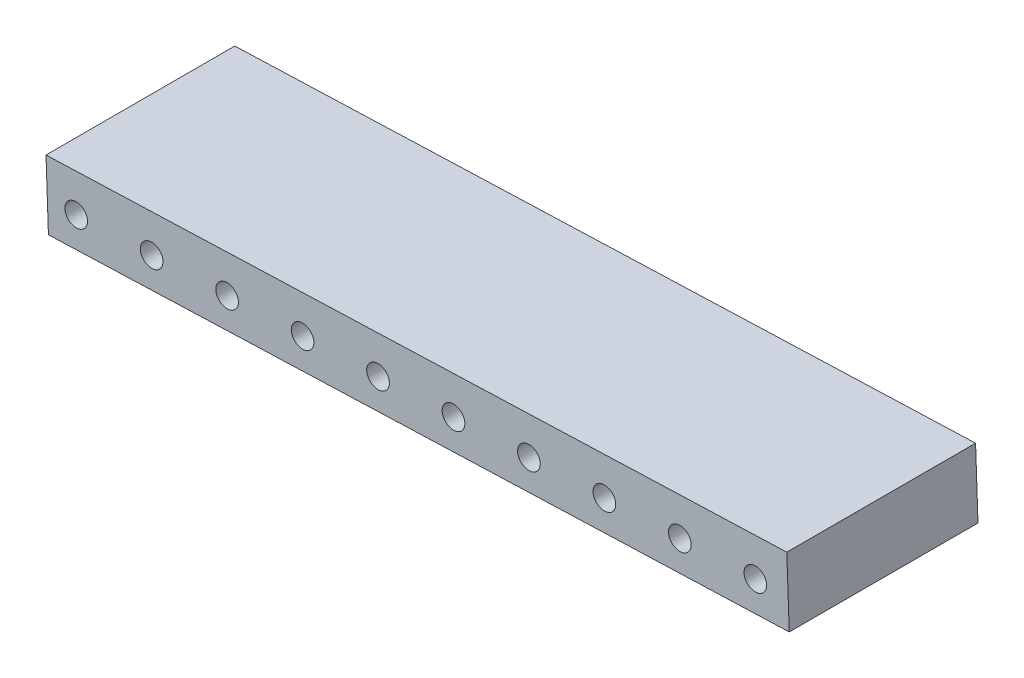
SolidWorks part; units mm, degrees
ref_plane "前视基准面" through (0, 0, 0) normal (0, 0, 1) x (1, 0, 0)
ref_plane "上视基准面" through (0, 0, 0) normal (0, 1, 0) x (1, 0, 0)
ref_plane "右视基准面" through (0, 0, 0) normal (1, 0, 0) x (0, 0, -1)
other "Configuration Table"
sketch "草图1" plane through (0, 0, 0) normal (0, 0, 1) x (1, 0, 0)
  line L0 (0, 0) -> (140, 0)
  line L1 (0, 35) -> (140, 25)
  line L2 (0, -35) -> (140, -25)
  circle A0 centre (0, 0) radius 35
  circle A1 centre (140, 0) radius 25
  dimension "D1" = 70
  dimension "D3" = 50
  dimension "D2" = 140
extrude "凸台-拉伸3" add sketch "草图1" along normal blind 5
sketch "草图4" plane through (0, 0, 5) normal (0, 0, 1) x (1, 0, 0)
  line L1 (-5, -5) -> (5, -5)
  line L2 (-5, -5) -> (-5, 5)
  line L3 (-5, 5) -> (5, 5)
  line L4 (5, -5) -> (5, 5)
  line L5 (-5, -5) -> (5, 5) construction
  line L6 (-5, 5) -> (5, -5) construction
  line L7 (135, -5) -> (145, -5)
  line L8 (135, -5) -> (135, 5)
  line L9 (135, 5) -> (145, 5)
  line L10 (145, -5) -> (145, 5)
  line L11 (135, -5) -> (145, 5) construction
  line L12 (135, 5) -> (145, -5) construction
  circle A0 centre (0, 0) radius 4
  circle A1 centre (-5, 5) radius 1.5
  circle A2 centre (5, 5) radius 1.5
  circle A3 centre (5, -5) radius 1.5
  circle A4 centre (-5, -5) radius 1.5
  circle A5 centre (140, 0) radius 4
  circle A6 centre (135, 5) radius 1.5
  circle A7 centre (145, 5) radius 1.5
  circle A8 centre (145, -5) radius 1.5
  circle A9 centre (135, -5) radius 1.5
  dimension "D1" = 8
  dimension "D4" = 3
  dimension "D6" = 8
  dimension "D9" = 3
  dimension "D2" = 10
  dimension "D3" = 10
  dimension "D7" = 10
  dimension "D8" = 10
  dimension "D5" = 4
  dimension "D10" = 4
extrude "切除-拉伸3" cut sketch "草图4" against normal blind 5 contours A5 | A0 | L2 A4 L1 | L1 A4 L2 | A6 | A9 | A8 | A7 | A1 | A2 | A3
sketch "草图5" plane through (0, 0, 5) normal (0, 0, 1) x (1, 0, 0)
  circle A0 centre (0, 0) radius 11
  circle A1 centre (140, 0) radius 11
  dimension "D1" = 22
  dimension "D2" = 22
extrude "切除-拉伸4" cut sketch "草图5" against normal blind 2
sketch "草图6" plane through (0, 0, 5) normal (0, 0, 1) x (1, 0, 0)
  circle A0 centre (0, 0) radius 30
  circle A1 centre (0, 30) radius 1.5
  circle A2 centre (15, 25.9808) radius 1.5
  circle A3 centre (25.9808, 15) radius 1.5
  circle A4 centre (30, 0) radius 1.5
  circle A5 centre (25.9808, -15) radius 1.5
  circle A6 centre (15, -25.9808) radius 1.5
  circle A7 centre (0, -30) radius 1.5
  circle A8 centre (-15, -25.9808) radius 1.5
  circle A9 centre (-25.9808, -15) radius 1.5
  circle A10 centre (-30, 0) radius 1.5
  circle A11 centre (-25.9808, 15) radius 1.5
  circle A12 centre (-15, 25.9808) radius 1.5
  circle A13 centre (140, 0) radius 20
  circle A14 centre (140, 20) radius 1.5
  circle A15 centre (150, 17.3205) radius 1.5
  circle A16 centre (157.3205, 10) radius 1.5
  circle A17 centre (160, 0) radius 1.5
  circle A18 centre (157.3205, -10) radius 1.5
  circle A19 centre (150, -17.3205) radius 1.5
  circle A20 centre (140, -20) radius 1.5
  circle A21 centre (130, -17.3205) radius 1.5
  circle A22 centre (122.6795, -10) radius 1.5
  circle A23 centre (120, 0) radius 1.5
  circle A24 centre (122.6795, 10) radius 1.5
  circle A25 centre (130, 17.3205) radius 1.5
  point P29 (0, 0)
  dimension "D1" = 60
  dimension "D2" = 3
  dimension "D4" = 40
  dimension "D5" = 3
  dimension "D3" = 12
  dimension "D6" = 12
extrude "切除-拉伸6" cut sketch "草图6" against normal through all contours A0 A12 | A11 | A1 | A2 | A3 | A4 | A5 | A6 | A7 | A8 | A9 | A10 | A25 | A14 | A15 | A16 | A17 | A18 | A19 | A20 | A21 | A22 | A23 | A24
sketch "草图7" plane through (0, 0, 5) normal (0, 0, 1) x (1, 0, 0)
  line L0 (140, 25) -> (0, 20)
  line L1 (140, -25) -> (0, -20)
  circle A0 centre (0, 0) radius 20
  circle A1 centre (140, 0) radius 25
  circle M1 centre (15, -25.9808) radius 1.5
  circle M2 centre (0, -30) radius 1.5
  circle M3 centre (-15, -25.9808) radius 1.5
  circle M4 centre (-25.9808, -15) radius 1.5
  circle M5 centre (-30, 0) radius 1.5
  circle M20 centre (15, 25.9808) radius 1.5
  circle M21 centre (-15, 25.9808) radius 1.5
  circle M22 centre (-25.9808, 15) radius 1.5
  circle M23 centre (0, 30) radius 1.5
  line M27 (0, -35) -> (140, -25)
  line M29 (140, 25) -> (0, 35)
  arc M30 (0, 35) -> (0, -35) centre (0, 0) ccw
  dimension "D1" = 40
extrude "切除-拉伸7" cut sketch "草图7" against normal blind 10 contours A1 L1 A0 L0 M29 M30 M27 M1 M3 M5 M21 M23 M22 M20 M4 M2
sketch "草图8" plane through (0, 0, 5) normal (0, 0, 1) x (1, 0, 0)
  circle A1 centre (0, 0) radius 11
extrude "切除-拉伸8" cut sketch "草图8" against normal blind 10
sketch "草图9" plane through (0, 0, 5) normal (0, 0, 1) x (1, 0, 0)
  circle A0 centre (0, 0) radius 15
  circle A1 centre (0, 15) radius 1.5
  circle A2 centre (10.6066, 10.6066) radius 1.5
  circle A3 centre (15, 0) radius 1.5
  circle A4 centre (10.6066, -10.6066) radius 1.5
  circle A5 centre (0, -15) radius 1.5
  circle A6 centre (-10.6066, -10.6066) radius 1.5
  circle A7 centre (-15, 0) radius 1.5
  circle A8 centre (-10.6066, 10.6066) radius 1.5
  dimension "D1" = 30
  dimension "D2" = 3
  dimension "D3" = 8
extrude "切除-拉伸9" cut sketch "草图9" against normal blind 10 contours A0 A4 | A2 | A3 | A5 | A6 | A7 | A8 | A1
sketch "草图10" plane through (0, 0, 3) normal (0, 0, 1) x (1, 0, 0)
  circle A0 centre (140, 0) radius 5
  dimension "D1" = 10
extrude "切除-拉伸10" cut sketch "草图10" against normal blind 10
sketch "草图11" plane through (0, 0, 5) normal (0, 0, 1) x (1, 0, 0)
  line L0 (140, 0) -> (110, 0)
  line L1 (140, 0) -> (130, 0)
  line L2 (110, 0) -> (105.5, 0)
  line L3 (150, -10) -> (110, -10)
  line L4 (150, -10) -> (150, 10)
  line L5 (150, 10) -> (110, 10)
  line L6 (110, -10) -> (110, 10)
  line L7 (150, -10) -> (110, 10) construction
  line L8 (150, 10) -> (110, -10) construction
  line L9 (105.5, 0) -> (105.5, 5)
  line L10 (130, -1000) -> (130, 49000) construction
  circle A0 centre (105.5, 5) radius 2
  circle A1 centre (105.5, -5) radius 2
  circle A2 centre (154.5, -5) radius 2
  circle A3 centre (154.5, 5) radius 2
  dimension "D6" = 4
  dimension "D1" = 30
  dimension "D2" = 10
  dimension "D3" = 20
  dimension "D4" = 4.5
  dimension "D5" = 5
extrude "切除-拉伸11" cut sketch "草图11" against normal blind 10
sketch "草图12" plane through (0, 0, 5) normal (0, 0, 1) x (1, 0, 0)
  line L0 (110, 10) -> (44831.3595, -22350.6798) construction
  line L1 (150, 10) -> (-44571.3595, -22350.6798) construction
  line L3 (109.5, -11) -> (150.5, -11)
  line L4 (109.5, -11) -> (109.5, 11)
  line L5 (109.5, 11) -> (150.5, 11)
  line L6 (150.5, -11) -> (150.5, 11)
  line L7 (109.5, -11) -> (150.5, 11) construction
  line L8 (109.5, 11) -> (150.5, -11) construction
  point P8 (130, 0)
  dimension "D1" = 41
  dimension "D2" = 22
extrude "切除-拉伸12" cut sketch "草图12" against normal blind 10
sketch "草图13" plane through (0, 0, 5) normal (0, 0, 1) x (1, 0, 0)
  line L0 (0.1785, -15.0032) -> (138.395, -19.9395)
  line L1 (0, -20) -> (138.2166, -24.9363)
  circle A0 centre (0, -15) radius 1.5
  circle A1 centre (9.9936, -15.3569) radius 1.5
  circle A2 centre (19.9873, -15.7138) radius 1.5
  circle A3 centre (29.9809, -16.0707) radius 1.5
  circle A4 centre (39.9745, -16.4277) radius 1.5
  circle A5 centre (49.9681, -16.7846) radius 1.5
  circle A6 centre (59.9618, -17.1415) radius 1.5
  circle A7 centre (69.9554, -17.4984) radius 1.5
  circle A8 centre (79.949, -17.8553) radius 1.5
  circle A9 centre (89.9427, -18.2122) radius 1.5
  circle A10 centre (99.9363, -18.5692) radius 1.5
  circle A11 centre (109.9299, -18.9261) radius 1.5
  circle A12 centre (119.9235, -19.283) radius 1.5
  circle A13 centre (129.9172, -19.6399) radius 1.5
  circle A14 centre (139.9108, -19.9968) radius 1.5
  circle M27 centre (130, -17.3205) radius 1.5
  dimension "D1" = 5
  dimension "D2" = 15
extrude "切除-拉伸13" cut sketch "草图13" against normal blind 10 contours L0 A1 | L0 A1 | L0 A13 | A13 L0 M27 | A2 | A3 | A4 | A5 | A6 | A7 | A9 | A8 | A10 | A11 | A12
sketch "草图14" plane through (0, 0, 5) normal (0, 0, 1) x (1, 0, 0)
  circle A0 centre (130, -17.3205) radius 1.5
  circle A1 centre (129.9172, -19.6399) radius 1.5
extrude "凸台-拉伸4" add sketch "草图14" against normal blind 5 contours A1 A0
sketch "草图15" plane through (0, 0, 5) normal (0, 0, 1) x (1, 0, 0)
  circle A0 centre (25.9808, 15) radius 1.5
  circle A1 centre (30, 0) radius 1.5
  circle A2 centre (25.9808, -15) radius 1.5
extrude "凸台-拉伸6" add sketch "草图15" against normal blind 5
sketch "草图16" plane through (0, 0, 5) normal (0, 0, 1) x (1, 0, 0)
  line L0 (0, 20) -> (140, 25)
  line L1 (0.1785, 15.0032) -> (140.1785, 20.0032)
  arc A0 (138.2166, -24.9363) -> (138.2166, 24.9363) centre (140, 0) ccw construction
  circle A1 centre (0, 15) radius 1.5
  circle A2 centre (9.9936, 15.3569) radius 1.5
  circle A3 centre (19.9873, 15.7138) radius 1.5
  circle A4 centre (29.9809, 16.0707) radius 1.5
  circle A5 centre (39.9745, 16.4277) radius 1.5
  circle A6 centre (49.9681, 16.7846) radius 1.5
  circle A7 centre (59.9618, 17.1415) radius 1.5
  circle A8 centre (69.9554, 17.4984) radius 1.5
  circle A9 centre (79.949, 17.8553) radius 1.5
  circle A10 centre (89.9427, 18.2122) radius 1.5
  circle A11 centre (99.9363, 18.5692) radius 1.5
  circle A12 centre (109.9299, 18.9261) radius 1.5
  circle A13 centre (119.9235, 19.283) radius 1.5
  circle A14 centre (129.9172, 19.6399) radius 1.5
  circle A15 centre (139.9108, 19.9968) radius 1.5
  dimension "D1" = 5
  dimension "D2" = 15
extrude "切除-拉伸14" cut sketch "草图16" against normal blind 5 contours L1 A6 | L1 A6 | L1 A7 | L1 A7 | L1 A8 | L1 A8 | A2 | A3 | A4 | A5 | A9 | A10 | A11 | A12 | A13 | A14
sketch "草图17" plane through (0, 0, 5) normal (0, 0, 1) x (1, 0, 0)
  circle A0 centre (130, 17.3205) radius 1.5
  circle A1 centre (129.9172, 19.6399) radius 1.5
extrude "凸台-拉伸7" add sketch "草图17" against normal blind 5 contours A1 A0
sketch "草图18" plane through (0, 0, 5) normal (0, 0, 1) x (1, 0, 0)
  line L2 (138.5735, 14.9427) -> (0.3569, 10.0064)
  line L3 (138.5735, 14.9427) -> (0.3569, 10.0064)
  line L5 (138.5735, -14.9427) -> (0.3569, -10.0064)
  line L6 (138.5735, -14.9427) -> (0.3569, -10.0064)
  circle A0 centre (0, 0) radius 25
  circle A1 centre (0, 0) radius 100
  dimension "D1" = 50
  dimension "D2" = 200
  dimension "D3" = 10
  dimension "D4" = 10
extrude "切除-拉伸15" cut sketch "草图18" against normal blind 5 contours L6 A1 L3 A0
sketch "草图19" plane through (0, 0, 5) normal (0, 0, 1) x (1, 0, 0)
  line L2 (99.0445, 14.5316) -> (22.5117, 11.7983)
  line L3 (134.9707, 15.8146) -> (6.5499, 11.2282)
  line L4 (16.3089, 11.5767) -> (15.9877, 20.571)
  line L5 (99.0445, -14.5316) -> (22.5117, -11.7983)
  line L6 (134.4063, -15.7945) -> (10.6063, -11.3731)
  line L7 (138.2166, 24.9363) -> (0, 20) construction
  line L8 (16.3089, -11.5767) -> (15.9877, -20.571)
  line L9 (138.2166, -24.9363) -> (0, -20) construction
  line L10 (15.9877, -20.571) -> (0, -20)
  line L11 (15.9877, 20.571) -> (0, 20)
  circle A1 centre (140, 0) radius 16.7558
  circle A2 centre (0, 0) radius 20
  dimension "D1" = 1
  dimension "D2" = 1
extrude "切除-拉伸19" cut sketch "草图19" against normal blind 5
sketch "草图21" plane through (0, 0, 5) normal (0, 0, 1) x (1, 0, 0)
  line L0 (134.4063, 15.7945) -> (134.0851, 24.7888)
  line L1 (138.2166, 24.9363) -> (15.9877, 20.571) construction
  line L2 (134.4063, -15.7945) -> (134.0851, -24.7888)
  line L3 (138.2166, -24.9363) -> (15.9877, -20.571) construction
  circle A0 centre (140, 0) radius 25
  arc M1 (156.2593, 4.0487) -> (156.2593, -4.0487) centre (140, 0) cw
  arc M2 (156.2593, -4.0487) -> (155.299, -6.8335) centre (154.5, -5) cw
  arc M3 (155.299, -6.8335) -> (134.4063, -15.7945) centre (140, 0) cw
  line M6 (15.9877, -20.571) -> (138.2166, -24.9363)
  arc M7 (138.2166, -24.9363) -> (138.2166, 24.9363) centre (140, 0) ccw
  line M8 (138.2166, 24.9363) -> (15.9877, 20.571)
  arc M11 (134.4063, 15.7945) -> (155.299, 6.8335) centre (140, 0) cw
  arc M12 (155.299, 6.8335) -> (156.2593, 4.0487) centre (154.5, 5) cw
  circle M37 centre (140, 20) radius 1.5
  circle M38 centre (150, 17.3205) radius 1.5
  circle M39 centre (157.3205, 10) radius 1.5
  circle M40 centre (160, 0) radius 1.5
  circle M41 centre (157.3205, -10) radius 1.5
  circle M42 centre (150, -17.3205) radius 1.5
  circle M43 centre (140, -20) radius 1.5
extrude "切除-拉伸20" cut sketch "草图21" against normal blind 5 contours A0 L0 L2 M7 M11 M12 M1 M2 M3 M38 M40 M42 M43 M41 M39 M37 | A0 L0 M8 | A0 L2 M6
sketch "草图22" plane through (0, 0, 0) normal (0, 0, -1) x (-1, 0, 0)
  line L0 (-134.0851, 24.7888) -> (-134.4063, 15.7945)
  line L1 (-134.4063, 15.7945) -> (-16.3089, 11.5767)
  line L2 (-16.3089, 11.5767) -> (-15.9877, 20.571)
  line L3 (-15.9877, 20.571) -> (-134.0851, 24.7888)
  line L4 (-134.4063, -15.7945) -> (-134.0851, -24.7888)
  line L5 (-134.0851, -24.7888) -> (-15.9877, -20.571)
  line L6 (-15.9877, -20.571) -> (-16.3089, -11.5767)
  line L7 (-16.3089, -11.5767) -> (-134.4063, -15.7945)
extrude "凸台-拉伸8" add sketch "草图22" along normal blind 10
sketch "草图23" plane through (0, 0, 5) normal (0, 0, 1) x (1, 0, 0)
  circle A0 centre (19.9873, 15.7138) radius 1.5
  circle A1 centre (29.9809, 16.0707) radius 1.5
  circle A2 centre (39.9745, 16.4277) radius 1.5
  circle A3 centre (49.9681, 16.7846) radius 1.5
  circle A4 centre (59.9618, 17.1415) radius 1.5
  circle A5 centre (69.9554, 17.4984) radius 1.5
  circle A6 centre (79.949, 17.8553) radius 1.5
  circle A7 centre (89.9427, 18.2122) radius 1.5
  circle A8 centre (99.9363, 18.5692) radius 1.5
  circle A9 centre (109.9299, 18.9261) radius 1.5
  circle A10 centre (119.9235, 19.283) radius 1.5
  circle A11 centre (129.9172, 19.6399) radius 1.5
  circle A12 centre (129.9172, -19.6399) radius 1.5
  circle A13 centre (119.9235, -19.283) radius 1.5
  circle A14 centre (109.9299, -18.9261) radius 1.5
  circle A15 centre (99.9363, -18.5692) radius 1.5
  circle A16 centre (89.9427, -18.2122) radius 1.5
  circle A17 centre (79.949, -17.8553) radius 1.5
  circle A18 centre (69.9554, -17.4984) radius 1.5
  circle A19 centre (59.9618, -17.1415) radius 1.5
  circle A20 centre (49.9681, -16.7846) radius 1.5
  circle A21 centre (39.9745, -16.4277) radius 1.5
  circle A22 centre (29.9809, -16.0707) radius 1.5
  circle A23 centre (19.9873, -15.7138) radius 1.5
extrude "切除-拉伸21" cut sketch "草图23" against normal blind 15
sketch "草图24" plane through (0, 0, -10) normal (0, 0, -1) x (-1, 0, 0)
  line L1 (-139.0544, 12.8066) -> (-138.879, 12.8066)
  line L2 (-139.0544, 12.8066) -> (-139.0544, -6.6664)
  line L3 (-139.0544, -6.6664) -> (-138.879, -6.6664)
  line L4 (-138.879, 12.8066) -> (-138.879, -6.6664)
  line L5 (-139.0544, 12.8066) -> (-138.879, -6.6664) construction
  line L6 (-139.0544, -6.6664) -> (-138.879, 12.8066) construction
  line L7 (-273.2608, -63.0482) -> (-10.2864, -63.0482)
  line L8 (-273.2608, -63.0482) -> (-273.2608, -7.8265)
  line L9 (-273.2608, -7.8265) -> (-10.2864, -7.8265)
  line L10 (-10.2864, -63.0482) -> (-10.2864, -7.8265)
  line L11 (-273.2608, -63.0482) -> (-10.2864, -7.8265) construction
  line L12 (-273.2608, -7.8265) -> (-10.2864, -63.0482) construction
  point P0 (-138.9667, 3.0701)
  point P5 (-141.7736, -35.4374)
extrude "切除-拉伸25" cut sketch "草图24" against normal through all both and the other way through all
sketch "草图25" plane through (0, 0, -10) normal (0, 0, -1) x (-1, 0, 0)
  line L0 (-134.0851, 24.7888) -> (-134.4063, 15.7945)
  line L1 (-134.4063, 15.7945) -> (-16.3089, 11.5767)
  line L2 (-16.3089, 11.5767) -> (-15.9877, 20.571)
  line L3 (-15.9877, 20.571) -> (-134.0851, 24.7888)
  line L4 (-129.9172, 19.6399) -> (49838.2255, -1764.9366) construction
  circle A0 centre (-129.9172, 19.6399) radius 1.5
  circle A1 centre (-119.9235, 19.283) radius 1.5
  circle A2 centre (-109.9299, 18.9261) radius 1.5
  circle A3 centre (-99.9363, 18.5692) radius 1.5
  circle A4 centre (-89.9427, 18.2122) radius 1.5
  circle A5 centre (-79.949, 17.8553) radius 1.5
  circle A6 centre (-69.9554, 17.4984) radius 1.5
  circle A7 centre (-59.9618, 17.1415) radius 1.5
  circle A8 centre (-49.9681, 16.7846) radius 1.5
  circle A9 centre (-39.9745, 16.4277) radius 1.5
  circle A10 centre (-29.9809, 16.0707) radius 1.5
  circle A11 centre (-19.9873, 15.7138) radius 1.5
  dimension "D1" = 12
extrude "凸台-拉伸9" add sketch "草图25" along normal blind 10
sketch "草图26" plane through (0, 0, -20) normal (0, 0, -1) x (-1, 0, 0)
  line L0 (-15.9877, 20.571) -> (-16.3089, 11.5767)
  line L1 (-23.9826, 20.8565) -> (-24.3038, 11.8623)
  line L4 (-33.9762, 21.2134) -> (-34.2974, 12.2192)
  line L5 (-33.9762, 21.2134) -> (-23.9826, 20.8565)
  line L6 (-34.2974, 12.2192) -> (-24.3038, 11.8623)
  line L7 (-134.0851, 24.7888) -> (-134.4063, 15.7945)
  line L8 (-114.0978, 24.0749) -> (-114.419, 15.0807)
  circle M10 centre (-129.9172, 19.6399) radius 1.5
  line M11 (-15.9877, 20.571) -> (-134.0851, 24.7888)
  line M12 (-134.0851, 24.7888) -> (-134.4063, 15.7945)
  line M13 (-134.4063, 15.7945) -> (-16.3089, 11.5767)
  circle M15 centre (-119.9235, 19.283) radius 1.5
  dimension "D2" = 10
  dimension "D1" = 8
  dimension "D3" = 20
extrude "切除-拉伸28" cut sketch "草图26" against normal through all both and the other way through all contours L8 M11 M12 M13 M10 M15
